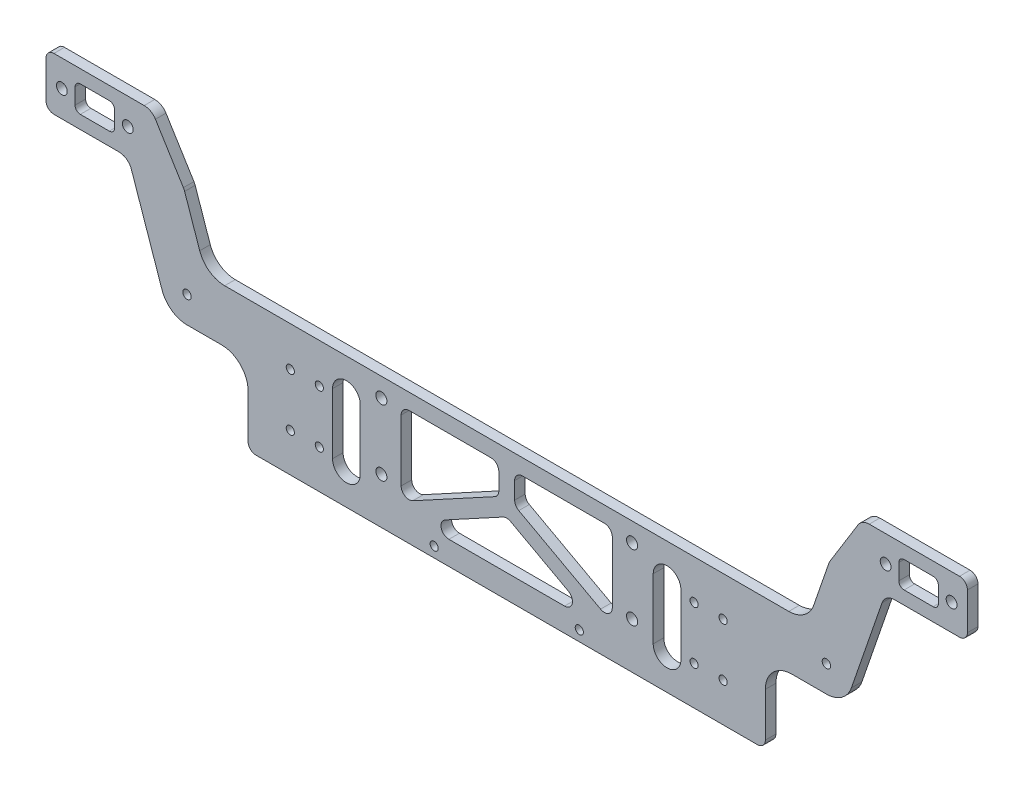
SolidWorks part; units mm, degrees
material "Thornel Mat VMA"
ref_plane "前视基准面" through (0, 0, 0) normal (0, 0, 1) x (1, 0, 0)
ref_plane "上视基准面" through (0, 0, 0) normal (0, 1, 0) x (1, 0, 0)
ref_plane "右视基准面" through (0, 0, 0) normal (1, 0, 0) x (0, 0, -1)
sketch "草图1" plane through (0, 0, 0) normal (0, 0, 1) x (1, 0, 0)
  line L1 (-98, -24.835) -> (98, -24.835)
  line L2 (-98, -24.835) -> (-98, 24.835)
  line L3 (-98, 24.835) -> (98, 24.835)
  line L4 (98, -24.835) -> (98, 24.835)
  line L5 (-98, -24.835) -> (98, 24.835) construction
  line L6 (-98, 24.835) -> (98, -24.835) construction
  point P0 (0, 0)
  dimension "D1" = 196
  dimension "D2" = 49.67
extrude "凸台-拉伸1" add sketch "草图1" along normal blind 4
sketch "草图2" plane through (0, 0, 4) normal (0, 0, 1) x (1, 0, 0)
  line L0 (98, 24.835) -> (114, 24.835)
  line L1 (114, 24.835) -> (122.2225, 48.715)
  line L2 (134.5666, 68.715) -> (174.5666, 68.715)
  line L3 (174.5666, 68.715) -> (174.5666, 48.715)
  line L4 (174.5666, 48.715) -> (143.375, 48.715)
  line L5 (143.375, 48.715) -> (128.2659, 4.835)
  line L6 (128.2659, 4.835) -> (98, 4.835)
  line L7 (98, -24.835) -> (98, 24.835) construction
  line L8 (98, 24.835) -> (98, 4.835)
  line L9 (0, 0) -> (0, 24.835) construction
  line L10 (98, 24.835) -> (-98, 24.835) construction
  line L11 (-98, 24.835) -> (-98, 4.835)
  line L12 (-128.2659, 4.835) -> (-98, 4.835)
  line L13 (-143.375, 48.715) -> (-128.2659, 4.835)
  line L14 (-174.5666, 48.715) -> (-143.375, 48.715)
  line L15 (-174.5666, 68.715) -> (-174.5666, 48.715)
  line L16 (-134.5666, 68.715) -> (-174.5666, 68.715)
  line L17 (-114, 24.835) -> (-122.2225, 48.715)
  line L18 (-98, 24.835) -> (-114, 24.835)
  line L19 (122.2225, 48.715) -> (143.375, 48.715) construction
  line L20 (-122.2225, 48.715) -> (-143.375, 48.715) construction
  line L21 (122.2225, 48.715) -> (134.5666, 68.715)
  line L23 (-122.2225, 48.715) -> (-134.5666, 68.715)
  dimension "D1" = 114
  dimension "D2" = 109
  dimension "D3" = 20
  dimension "D4" = 20
  dimension "D5" = 20
  dimension "D6" = 43.88
  dimension "D7" = 40
  dimension "D8" = 18
extrude "凸台-拉伸2" add sketch "草图2" against normal up to surface (4 mm away) up to face at (0, 0, 0)
fillet "圆角1" radius 10 4 edges at (128.2659, 4.835, 2) (114, 24.835, 2) (-128.2659, 4.835, 2) (-114, 24.835, 2)
fillet "圆角2" radius 3 6 edges at (-174.5666, 48.715, 2) (-174.5666, 68.715, 2) (174.5666, 68.715, 2) (174.5666, 48.715, 2) (98, -24.835, 2) (-98, -24.835, 2)
sketch "草图3" plane through (0, 0, 4) normal (0, 0, 1) x (1, 0, 0)
  line L0 (98, -21.835) -> (98, 4.835) construction
  line L1 (-88, -15) -> (88, -15) construction
  line L2 (-88, -15) -> (-88, 15) construction
  line L3 (-88, 15) -> (88, 15) construction
  line L4 (88, -15) -> (88, 15) construction
  line L5 (-88, -15) -> (88, 15) construction
  line L6 (-88, 15) -> (88, -15) construction
  circle A0 centre (88, -15) radius 1.6
  circle A1 centre (88, 15) radius 1.6
  circle A2 centre (-88, 15) radius 1.6
  circle A3 centre (-88, -15) radius 1.6
  point P0 (0, 0)
  dimension "D3" = 3.2
  dimension "D1" = 10
  dimension "D2" = 30
sketch "草图4" plane through (0, 0, 4) normal (0, 0, 1) x (1, 0, 0)
  line L0 (0, 5.1613) -> (0, 0) construction
  line L1 (47.5, -7.3387) -> (-47.5, -7.3387) construction
  line L2 (47.5, -7.3387) -> (47.5, 17.6613) construction
  line L3 (47.5, 17.6613) -> (-47.5, 17.6613) construction
  line L4 (-47.5, -7.3387) -> (-47.5, 17.6613) construction
  line L5 (47.5, -7.3387) -> (-47.5, 17.6613) construction
  line L6 (47.5, 17.6613) -> (-47.5, -7.3387) construction
  circle A2 centre (47.5, -7.3387) radius 2.1
  circle A3 centre (47.5, 17.6613) radius 2.1
  circle A4 centre (-47.5, 17.6613) radius 2.1
  circle A5 centre (-47.5, -7.3387) radius 2.1
  point P6 (0, 5.1613)
  dimension "D4" = 4.2
  dimension "D1" = 95
  dimension "D2" = 25
  dimension "D3" = 5.1613
extrude "切除-拉伸2" cut sketch "草图4" against normal blind 4
fillet "圆角3" radius 5 6 edges at (122.2225, 48.715, 2) (-122.2225, 48.715, 2) (-134.5666, 68.715, 2) (-143.375, 48.715, 2) (134.5666, 68.715, 2) (143.375, 48.715, 2)
sketch "草图5" plane through (0, 0, 4) normal (0, 0, 1) x (1, 0, 0)
  line L0 (0, 0) -> (0, -20.895) construction
  line L1 (0, -20.895) -> (27.5, -20.895) construction
  line L2 (-95, -24.835) -> (95, -24.835) construction
  circle A0 centre (27.5, -20.895) radius 1.55
  circle A1 centre (-27.5, -20.895) radius 1.55
  dimension "D3" = 3.1
  dimension "D1" = 27.5
  dimension "D2" = 3.94
extrude "切除-拉伸3" cut sketch "草图5" against normal blind 10
sketch "草图6" [suppressed] plane through (0, 0, 4) normal (0, 0, 1) x (1, 0, 0)
  line L0 (-174.5666, 58.715) -> (-128.3946, 58.715) construction
  line L1 (-174.5666, 65.715) -> (-174.5666, 51.715) construction
  line L2 (-122.5144, 49.1879) -> (-133.1014, 66.3411) construction
  line L3 (0, 0) -> (0, 128.8135) construction
  line L4 (174.5666, 58.715) -> (128.3946, 58.715) construction
  circle A0 centre (-168.5666, 58.715) radius 2.05
  circle A1 centre (-143.5666, 58.715) radius 2.05
  circle A2 centre (143.5666, 58.715) radius 2.05
  circle A3 centre (168.5666, 58.715) radius 2.05
  dimension "D1" = 4.1
  dimension "D2" = 6
  dimension "D3" = 25
extrude "切除-拉伸4" [suppressed] cut sketch "草图6" against normal blind 10
sketch "草图7" plane through (0, 0, 4) normal (0, 0, 1) x (1, 0, 0)
  line L0 (-174.5666, 58.715) -> (-136.4981, 58.715) construction
  line L1 (-174.5666, 65.715) -> (-174.5666, 51.715) construction
  line L2 (0, 0) -> (0, 175.8145) construction
  line L3 (174.5666, 58.715) -> (136.4981, 58.715) construction
  circle A0 centre (-168.5666, 58.715) radius 2.05
  circle A1 centre (-143.5666, 58.715) radius 2.05
  circle A2 centre (143.5666, 58.715) radius 2.05
  circle A3 centre (168.5666, 58.715) radius 2.05
  dimension "D1" = 4.1
  dimension "D2" = 6
  dimension "D3" = 25
extrude "切除-拉伸5" cut sketch "草图7" against normal blind 102
sketch "草图8" plane through (0, 0, 4) normal (0, 0, 1) x (1, 0, 0)
  line L0 (106.8671, 24.835) -> (-106.8671, 24.835) construction
  line L1 (-40, -15.895) -> (40, -15.895)
  line L2 (-40, -15.895) -> (-40, 18.835)
  line L3 (-40, 18.835) -> (40, 18.835)
  line L4 (40, -15.895) -> (40, 18.835)
  line L5 (-40, -15.895) -> (40, 18.835) construction
  line L6 (-40, 18.835) -> (40, -15.895) construction
  line L7 (0, 1.47) -> (0, 18.835) construction
  line L8 (0, 5.835) -> (-40, -15.895) construction
  line L9 (0, 5.835) -> (40, -15.895) construction
  line L10 (3, 1.47) -> (3, 18.835)
  line L11 (0, 9.2491) -> (41.4321, -13.2589)
  line L12 (0, 9.2491) -> (-41.4321, -13.2589)
  line L13 (-3, 1.47) -> (-3, 18.835)
  line L14 (0, 2.4209) -> (38.5679, -18.5311)
  line L15 (0, 2.4209) -> (-38.5679, -18.5311)
  circle A0 centre (-27.5, -20.895) radius 1.55 construction
  circle A1 centre (-47.5, -7.3387) radius 2.1 construction
  point P0 (0, 1.47)
  dimension "D2" = 7.5
  dimension "D1" = 5
  dimension "D3" = 6
  dimension "D4" = 13
  dimension "D5" = 3
  dimension "D6" = 3
extrude "切除-拉伸8" cut sketch "草图8" against normal blind 10 contours L12 L13 L3 L2 | L14 L15 L1 | L10 L11 L4 L3
fillet "圆角4" radius 3 11 edges at (-33.7154, -15.895, 2) (0, 2.4209, 2) (33.7154, -15.895, 2) (40, 18.835, 2) (40, -12.4809, 2) (3, 7.6194, 2) (3, 18.835, 2) (-3, 18.835, 2) (-3, 7.6194, 2) (-40, 18.835, 2) (-40, -12.4809, 2)
sketch "草图10" [suppressed] plane through (0, 0, 4) normal (0, 0, 1) x (1, 0, 0)
  line L0 (106.8671, 24.835) -> (-106.8671, 24.835) construction
  line L1 (-40, -17.835) -> (40, -17.835)
  line L2 (-40, -17.835) -> (-40, 18.835)
  line L3 (-40, 18.835) -> (40, 18.835)
  line L4 (40, -17.835) -> (40, 18.835)
  line L5 (-40, -17.835) -> (40, 18.835) construction
  line L6 (-40, 18.835) -> (40, -17.835) construction
  line L7 (-95, -24.835) -> (95, -24.835) construction
  line L8 (0, 18.835) -> (0, 6.835) construction
  line L9 (0, 6.835) -> (-40, -17.835) construction
  line L10 (0, 6.835) -> (40, -17.835) construction
  line L11 (-3, 18.835) -> (-3, 6.835)
  line L12 (-1.5748, 9.3884) -> (-41.5748, -15.2816)
  line L13 (-1.5748, 4.2816) -> (38.4252, -20.3884)
  line L14 (3, 18.835) -> (3, 6.835)
  line L15 (1.5748, 4.2816) -> (-38.4252, -20.3884)
  line L16 (1.5748, 9.3884) -> (41.5748, -15.2816)
  circle A0 centre (-47.5, -7.3387) radius 2.1 construction
  circle A1 centre (47.5, 17.6613) radius 2.1 construction
  point P0 (0, 0.5)
  dimension "D1" = 6
  dimension "D2" = 7
  dimension "D3" = 7.5
  dimension "D4" = 7.5
  dimension "D5" = 12
  dimension "D6" = 3
  dimension "D7" = 3
extrude "切除-拉伸10" [suppressed] cut sketch "草图10" against normal blind 10 contours L13 L15 L1 | L12 L11 L3 L2 | L14 L16 L4 L3
fillet "圆角7" [suppressed] radius 2
sketch "草图13" [suppressed] plane through (0, 0, 4) normal (0, 0, 1) x (1, 0, 0)
  line L0 (106.8671, 24.835) -> (-106.8671, 24.835) construction
  line L1 (-98, 4.835) -> (-104, 4.835)
  line L2 (-98, 4.835) -> (-98, -15.165)
  line L3 (-98, -15.165) -> (-104, -15.165)
  line L4 (-104, 4.835) -> (-104, -15.165)
  dimension "D1" = 40
  dimension "D2" = 6
extrude "凸台-拉伸3" [suppressed] add sketch "草图13" against normal up to surface (4 mm away)
mirror "镜向3" [suppressed] about plane through (0, 0, 0) normal (1, 0, 0)
fillet "圆角9" [suppressed] radius 10
fillet "圆角10" [suppressed] radius 2
sketch "草图14" [suppressed] plane through (0, 0, 0) normal (0, 0, -1) x (-1, 0, 0)
  line L0 (104, 24.835) -> (104, 9.835) construction
  line L1 (-106.8671, 24.835) -> (106.8671, 24.835) construction
  line L2 (104, 9.835) -> (104, -10.165) construction
  circle A2 centre (104, 9.835) radius 1.55
  circle A3 centre (104, -10.165) radius 1.55
  dimension "D4" = 3.1
  dimension "D1" = 104
  dimension "D2" = 15
  dimension "D3" = 20
extrude "切除-拉伸12" [suppressed] cut sketch "草图14" against normal blind 10
mirror "镜向4" [suppressed] about plane through (0, 0, 0) normal (1, 0, 0)
sketch "草图15" plane through (0, 0, 0) normal (0, 0, -1) x (-1, 0, 0)
  line L0 (-106.8671, 24.835) -> (106.8671, 24.835) construction
  line L1 (-98, 4.835) -> (-104, 4.835)
  line L2 (-98, 4.835) -> (-98, -15.165)
  line L3 (-98, -15.165) -> (-104, -15.165)
  line L4 (-104, 4.835) -> (-104, -15.165)
  dimension "D1" = 40
  dimension "D2" = 6
extrude "凸台-拉伸4" add sketch "草图15" against normal up to surface (4 mm away) up to face at (21.1904, 8.471, 4)
mirror "镜向5" about plane through (0, 0, 0) normal (1, 0, 0) of "凸台-拉伸4"
fillet "圆角11" radius 10 2 edges at (-104, 4.835, 2) (104, 4.835, 2)
fillet "圆角12" radius 2 4 edges at (-104, -15.165, 2) (-98, -15.165, 2) (104, -15.165, 2) (98, -15.165, 2)
sketch "草图16" plane through (0, 0, 4) normal (0, 0, 1) x (1, 0, 0)
  line L0 (0, 0) -> (104, 0) construction
  line L1 (104, 0) -> (104, 9.835) construction
  line L2 (104, 0) -> (104, -10.165) construction
  circle A2 centre (104, -10.165) radius 1.6
  circle A3 centre (104, 9.835) radius 1.6
  dimension "D4" = 3.2
  dimension "D1" = 104
  dimension "D2" = 9.835
  dimension "D3" = 10.165
extrude "切除-拉伸13" cut sketch "草图16" against normal blind 10
mirror "镜向6" about plane through (0, 0, 0) normal (1, 0, 0) of "切除-拉伸13"
sketch "草图21" [suppressed] plane through (0, 0, 4) normal (0, 0, 1) x (1, 0, 0)
  line L0 (-114, 4.835) -> (-98, 4.835)
  line L1 (-98, 4.835) -> (-98, -17.165)
  line L2 (-114, 4.835) -> (-114, -17.165)
  line L3 (-114, -17.165) -> (-98, -17.165)
extrude "切除-拉伸16" [suppressed] cut sketch "草图21" against normal blind 10
sketch "草图22" [suppressed] plane through (0, 0, 4) normal (0, 0, 1) x (1, 0, 0)
  circle A0 centre (-104, 9.835) radius 1.55 construction
  circle A1 centre (-104, 9.835) radius 1.55
extrude "凸台-拉伸5" [suppressed] add sketch "草图22" against normal up to surface (4 mm away)
fillet "圆角13" [suppressed] radius 10
mirror "镜向9" [suppressed] about plane through (0, 0, 0) normal (1, 0, 0)
sketch "草图23" plane through (0, 0, 4) normal (0, 0, 1) x (1, 0, 0)
  line L0 (-114, 4.835) -> (-98, 4.835)
  line L1 (-98, 4.835) -> (-98, -17.165)
  line L2 (-114, 4.835) -> (-114, -17.165)
  line L3 (-114, -17.165) -> (-98, -17.165)
  line L4 (0, -0.9932) -> (0, 64.1074) construction
  line L5 (114, -17.165) -> (98, -17.165)
  line L6 (114, 4.835) -> (114, -17.165)
  line L7 (98, 4.835) -> (98, -17.165)
  line L8 (114, 4.835) -> (98, 4.835)
extrude "切除-拉伸17" cut sketch "草图23" against normal blind 10
sketch "草图24" plane through (0, 0, 4) normal (0, 0, 1) x (1, 0, 0)
  circle A0 centre (104, 9.835) radius 1.6 construction
  circle A1 centre (-104, 9.835) radius 1.6 construction
  circle A2 centre (104, 9.835) radius 1.6
  circle A3 centre (-104, 9.835) radius 1.6
extrude "凸台-拉伸6" add sketch "草图24" against normal up to surface (4 mm away) up to face at (0, 34.7071, 0)
fillet "圆角14" radius 10 2 edges at (98, 4.835, 2) (-98, 4.835, 2)
sketch "草图25" plane through (0, 0, 4) normal (0, 0, 1) x (1, 0, 0)
  line L0 (-168.7548, 58.715) -> (-143.3784, 58.715) construction
  line L1 (0, 0) -> (0, 119.1313) construction
  line L8 (-163.5666, 53.715) -> (-148.5666, 53.715)
  line L9 (-163.5666, 53.715) -> (-163.5666, 63.715)
  line L10 (-163.5666, 63.715) -> (-148.5666, 63.715)
  line L11 (-148.5666, 53.715) -> (-148.5666, 63.715)
  line L12 (-156.0666, 63.715) -> (-156.0666, 53.715) construction
  line L13 (-163.5666, 58.715) -> (-148.5666, 58.715) construction
  line L14 (163.5666, 63.715) -> (148.5666, 63.715)
  line L15 (148.5666, 53.715) -> (148.5666, 63.715)
  line L16 (163.5666, 53.715) -> (148.5666, 53.715)
  line L17 (163.5666, 53.715) -> (163.5666, 63.715)
  point P2 (-156.0666, 58.715)
extrude "切除-拉伸18" cut sketch "草图25" against normal blind 10
sketch "草图26" [suppressed] plane through (0, 0, 3) normal (0, 0, 1) x (1, 0, 0)
  line L0 (116.3223, 31.5793) -> (109.6366, 12.1628)
  line L1 (-98, 38.2485) -> (98, 38.2485)
  line L2 (-98, 38.2485) -> (-98, -38.2485)
  line L3 (-98, -38.2485) -> (98, -38.2485)
  line L4 (98, 38.2485) -> (98, -38.2485)
  line L5 (-98, 38.2485) -> (98, -38.2485) construction
  line L6 (-98, -38.2485) -> (98, 38.2485) construction
  line L7 (130.5881, 11.5793) -> (122.2513, -12.6326)
  line L8 (130.5881, 11.5793) -> (142.2138, 45.3428) construction
  line L9 (122.2513, -12.6326) -> (69.9937, -12.6326)
  line L10 (69.9937, -12.6326) -> (69.9937, 12.1628)
  line L11 (69.9937, 12.1628) -> (109.6366, 12.1628)
  line L12 (130.5881, 11.5793) -> (116.3223, 31.5793)
  point P0 (0, 0)
sketch "草图27" plane through (0, 0, 0) normal (0, 0, -1) x (-1, 0, 0)
  line L0 (0, 0) -> (0, -43.4343) construction
  circle A2 centre (-82, -10.165) radius 1.55
  circle A3 centre (-82, 9.835) radius 1.55
  circle A4 centre (82, 9.835) radius 1.55
  circle A5 centre (82, -10.165) radius 1.55
  circle A12 centre (-71, 9.835) radius 1.55
  circle A13 centre (-71, -10.165) radius 1.55
  circle A14 centre (71, -10.165) radius 1.55
  circle A15 centre (71, 9.835) radius 1.55
  dimension "D1" = 3.1
extrude "切除-拉伸19" cut sketch "草图27" against normal blind 5
sketch "草图29" [suppressed] plane through (0, 0, 4) normal (0, 0, 1) x (1, 0, 0)
  line L0 (136.401, 28.4611) -> (117.4906, 34.9724) construction
  line L1 (130.5881, 11.5793) -> (142.2138, 45.3428) construction
  line L2 (122.0416, 48.1896) -> (116.3223, 31.5793) construction
  line L3 (126.9458, 31.7168) -> (121.1329, 14.835) construction
  line L4 (106.8671, 24.835) -> (-106.8671, 24.835) construction
  line L6 (0, -34.693) -> (0, 45.1501) construction
  circle A0 centre (121.1329, 14.835) radius 1.6
  circle A1 centre (-121.1329, 14.835) radius 1.6
  dimension "D1" = 3.2
  dimension "D2" = 10
extrude "切除-拉伸21" [suppressed] cut sketch "草图29" against normal blind 10
sketch "草图30" plane through (0, 0, 4) normal (0, 0, 1) x (1, 0, 0)
  line L0 (106.8671, 24.835) -> (-106.8671, 24.835) construction
  line L1 (130.5881, 11.5793) -> (142.2138, 45.3428) construction
  line L2 (136.401, 28.4611) -> (117.4906, 34.9724) construction
  line L3 (122.0416, 48.1896) -> (116.3223, 31.5793) construction
  line L4 (126.9458, 31.7168) -> (121.1329, 14.835) construction
  line L5 (0, -36.5817) -> (0, 39.8537) construction
  circle A0 centre (121.1329, 14.835) radius 1.6
  circle A1 centre (-121.1329, 14.835) radius 1.6
  dimension "D3" = 3.2
  dimension "D1" = 10
extrude "切除-拉伸22" cut sketch "草图30" against normal blind 10
fillet "圆角15" radius 2 8 edges at (148.5666, 53.715, 2) (148.5666, 63.715, 2) (163.5666, 63.715, 2) (-148.5666, 53.715, 2) (-163.5666, 53.715, 2) (-163.5666, 63.715, 2) (-148.5666, 63.715, 2) (163.5666, 53.715, 2)
sketch "草图31" plane through (0, 0, 4) normal (0, 0, 1) x (1, 0, 0)
  line L0 (60.75, 11.5) -> (60.75, -11.5) construction
  line L1 (66, 11.5) -> (66, -11.5)
  line L2 (55.5, 11.5) -> (55.5, -11.5)
  line L3 (0, -35.9103) -> (0, 39.133) construction
  line L4 (-60.75, 11.5) -> (-60.75, -11.5) construction
  line L5 (-66, 11.5) -> (-66, -11.5)
  line L6 (-55.5, 11.5) -> (-55.5, -11.5)
  arc A0 (66, 11.5) -> (55.5, 11.5) centre (60.75, 11.5) ccw
  arc A1 (55.5, -11.5) -> (66, -11.5) centre (60.75, -11.5) ccw
  circle A2 centre (47.5, -7.3387) radius 2.1 construction
  circle A3 centre (71, -10.165) radius 1.55 construction
  arc A4 (-66, 11.5) -> (-55.5, 11.5) centre (-60.75, 11.5) cw
  arc A5 (-55.5, -11.5) -> (-66, -11.5) centre (-60.75, -11.5) cw
  point P2 (60.75, 0)
  point P16 (-60.75, 0)
  dimension "D1" = 8
  dimension "D2" = 5
  dimension "D3" = 23
extrude "切除-拉伸23" cut sketch "草图31" against normal blind 10
